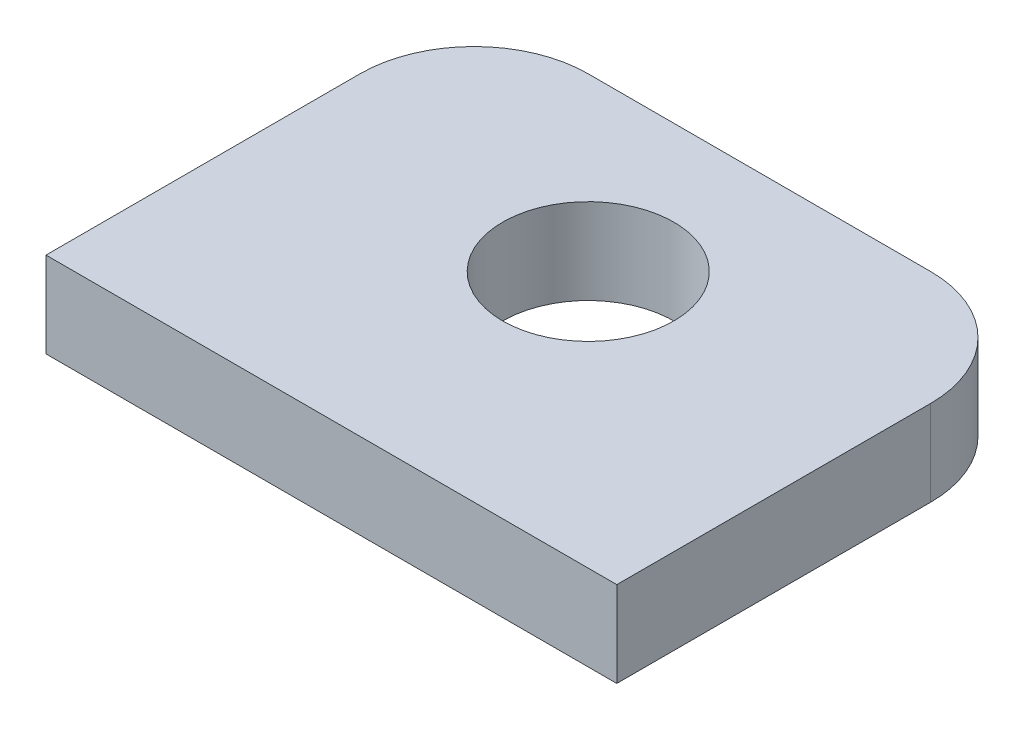
SolidWorks part; units mm, degrees
ref_plane "Plano frontal" through (0, 0, 0) normal (0, 0, 1) x (1, 0, 0)
ref_plane "Plano superior" through (0, 0, 0) normal (0, 1, 0) x (1, 0, 0)
ref_plane "Plano direito" through (0, 0, 0) normal (1, 0, 0) x (0, 0, -1)
sketch "Esboço1" plane through (0, 0, 0) normal (0, 1, 0) x (1, 0, 0)
  line L0 (-5, -3.75) -> (-5, 1.75)
  line L1 (-5, -3.75) -> (5, -3.75)
  line L2 (-3, 3.75) -> (3, 3.75)
  line L3 (5, -3.75) -> (5, 1.75)
  line L4 (-5, -3.75) -> (5, 3.75) construction
  line L5 (-5, 3.75) -> (5, -3.75) construction
  circle A0 centre (0, 0.75) radius 1.5
  arc A1 (3, 3.75) -> (5, 1.75) centre (3, 1.75) cw
  arc A2 (-5, 1.75) -> (-3, 3.75) centre (-3, 1.75) cw
  point P1 (0, 0)
  dimension "D3" = 3
  dimension "D6" = 2
  dimension "D1" = 7.5
  dimension "D2" = 10
  dimension "D4" = 3
  dimension "D5" = 5
extrude "Ressalto-extrusão1" add sketch "Esboço1" along normal blind 1.5
